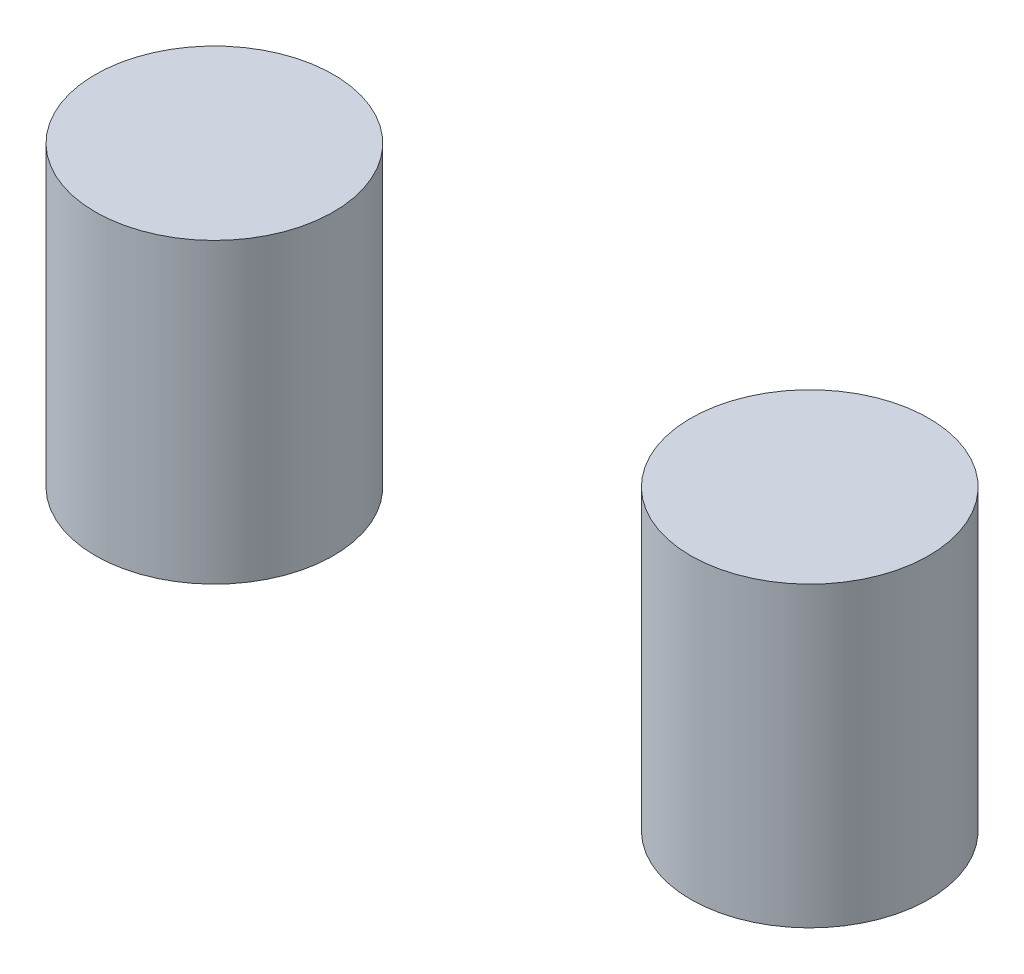
SolidWorks part; units mm, degrees
ref_plane "Front Plane" through (0, 0, 0) normal (0, 0, 1) x (1, 0, 0)
ref_plane "Top Plane" through (0, 0, 0) normal (0, 1, 0) x (1, 0, 0)
ref_plane "Right Plane" through (0, 0, 0) normal (1, 0, 0) x (0, 0, -1)
sketch "Sketch1" plane through (0, 0, 0) normal (0, 1, 0) x (1, 0, 0)
  circle A1 centre (10, 0) radius 4
  circle A2 centre (-10, 0) radius 4
  point P0 (0, 0)
  point P7 (0, 0)
  point P9 (6.014, -0.3342)
  dimension "D1" = 10
  dimension "D4" = 8
  dimension "D2" = 10
extrude "Boss-Extrude1" add sketch "Sketch1" along normal blind 10
